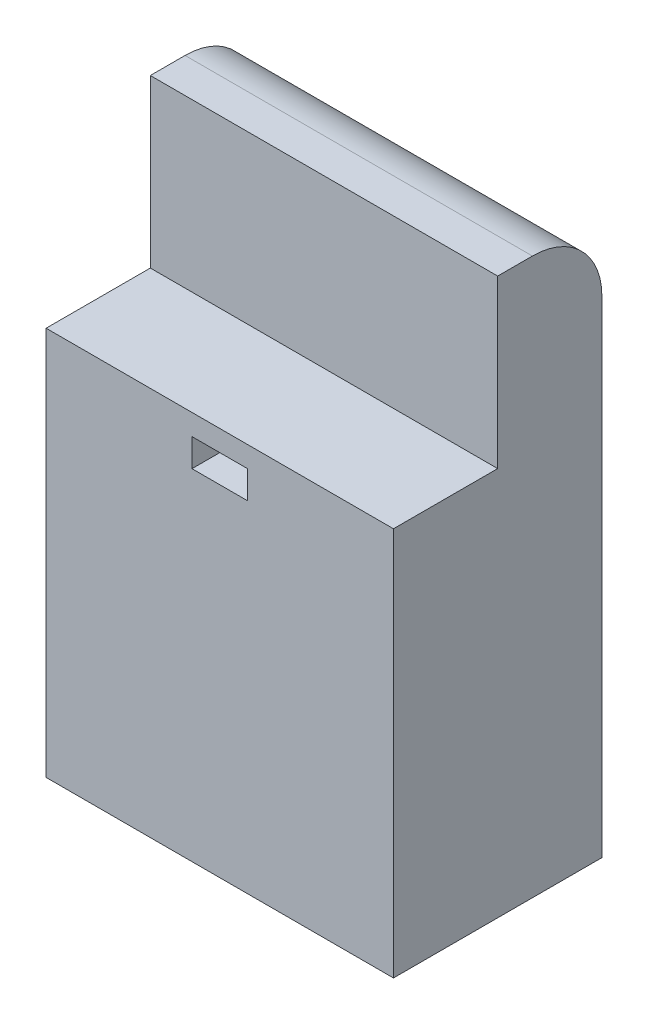
SolidWorks part; units mm, degrees
ref_plane "Ebene vorne" through (0, 0, 0) normal (0, 0, 1) x (1, 0, 0)
ref_plane "Ebene oben" through (0, 0, 0) normal (0, 1, 0) x (1, 0, 0)
ref_plane "Ebene rechts" through (0, 0, 0) normal (1, 0, 0) x (0, 0, -1)
sketch "Skizze1" plane through (0, 0, 0) normal (0, 1, 0) x (1, 0, 0)
  line L1 (12.5, -7.5) -> (-12.5, -7.5)
  line L2 (12.5, -7.5) -> (12.5, 7.5)
  line L3 (12.5, 7.5) -> (-12.5, 7.5)
  line L4 (-12.5, -7.5) -> (-12.5, 7.5)
  line L5 (12.5, -7.5) -> (-12.5, 7.5) construction
  line L6 (12.5, 7.5) -> (-12.5, -7.5) construction
  point P0 (0, 0)
  dimension "D1" = 15
  dimension "D2" = 25
extrude "Aufsatz-Linear austragen1" add sketch "Skizze1" along normal blind 40
sketch "Skizze2" plane through (0, 40, 0) normal (0, 1, 0) x (1, 0, 0)
  line L0 (12.5, -7.5) -> (12.5, 7.5) construction
  line L1 (-12.5, -7.5) -> (12.5, -7.5)
  line L2 (-12.5, -7.5) -> (-12.5, 0)
  line L3 (-12.5, 0) -> (12.5, 0)
  line L4 (12.5, -7.5) -> (12.5, 0)
extrude "Schnitt-Linear austragen1" cut sketch "Skizze2" against normal blind 12
fillet "Verrundung1" radius 5 1 edges at (0, 40, -7.5)
sketch "Skizze3" plane through (0, 0, 7.5) normal (0, 0, 1) x (1, 0, 0)
  line L1 (-2, 24.4947) -> (2, 24.4947)
  line L2 (-2, 24.4947) -> (-2, 26.4947)
  line L3 (-2, 26.4947) -> (2, 26.4947)
  line L4 (2, 24.4947) -> (2, 26.4947)
  line L5 (-2, 24.4947) -> (2, 26.4947) construction
  line L6 (-2, 26.4947) -> (2, 24.4947) construction
  point P0 (0, 25.4947)
  dimension "D1" = 2
  dimension "D2" = 4
extrude "Schnitt-Linear austragen2" cut sketch "Skizze3" against normal through all
